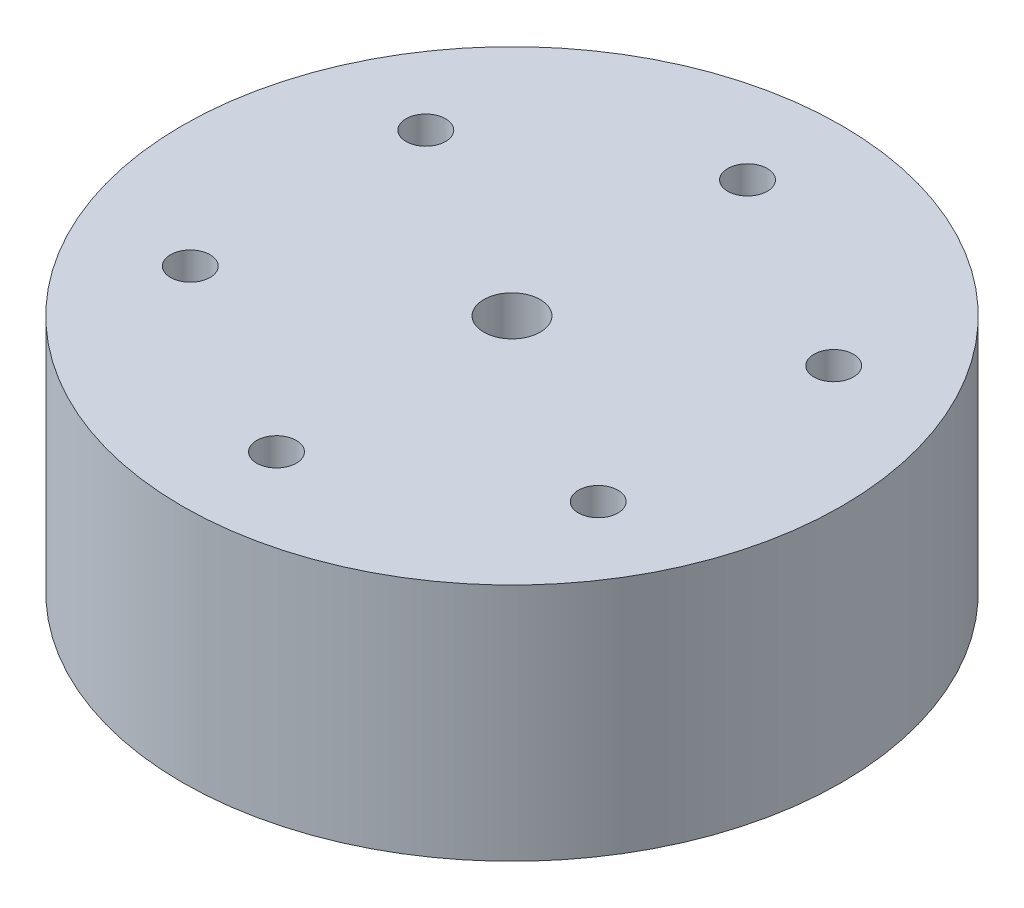
SolidWorks part; units mm, degrees
ref_plane "Front Plane" through (0, 0, 0) normal (0, 0, 1) x (1, 0, 0)
ref_plane "Top Plane" through (0, 0, 0) normal (0, 1, 0) x (1, 0, 0)
ref_plane "Right Plane" through (0, 0, 0) normal (1, 0, 0) x (0, 0, -1)
sketch "Sketch2" plane through (0, 0, 0) normal (0, 1, 0) x (1, 0, 0)
  circle A0 centre (0, 0) radius 35
  dimension "D1" = 70
extrude "Boss-Extrude1" add sketch "Sketch2" along normal blind 25.4
sketch "Sketch3" plane through (0, 25.4, 0) normal (0, 1, 0) x (1, 0, 0)
  line L0 (0, -3) -> (0, 2.5) construction
  arc A0 (-1.6583, 2.5) -> (1.6583, 2.5) centre (0, 0) ccw
  arc A1 (1.6583, 2.5) -> (-1.6583, 2.5) centre (0, 0) ccw
  dimension "D1" = 6
  dimension "D2" = 5.5
extrude "Cut-Extrude1" cut sketch "Sketch3" against normal through all
sketch "Sketch5" plane through (0, 25.4, 0) normal (0, 1, 0) x (1, 0, 0)
  circle A0 centre (0, 0) radius 25 construction
  circle A1 centre (0, 25) radius 2.1
  circle A2 centre (21.6506, 12.5) radius 2.1
  circle A3 centre (21.6506, -12.5) radius 2.1
  circle A4 centre (0, -25) radius 2.1
  circle A5 centre (-21.6506, -12.5) radius 2.1
  circle A6 centre (-21.6506, 12.5) radius 2.1
  point P17 (0, 0)
  dimension "D1" = 50
  dimension "D2" = 4.2
  dimension "D3" = 6
extrude "Cut-Extrude3" cut sketch "Sketch5" against normal through all
